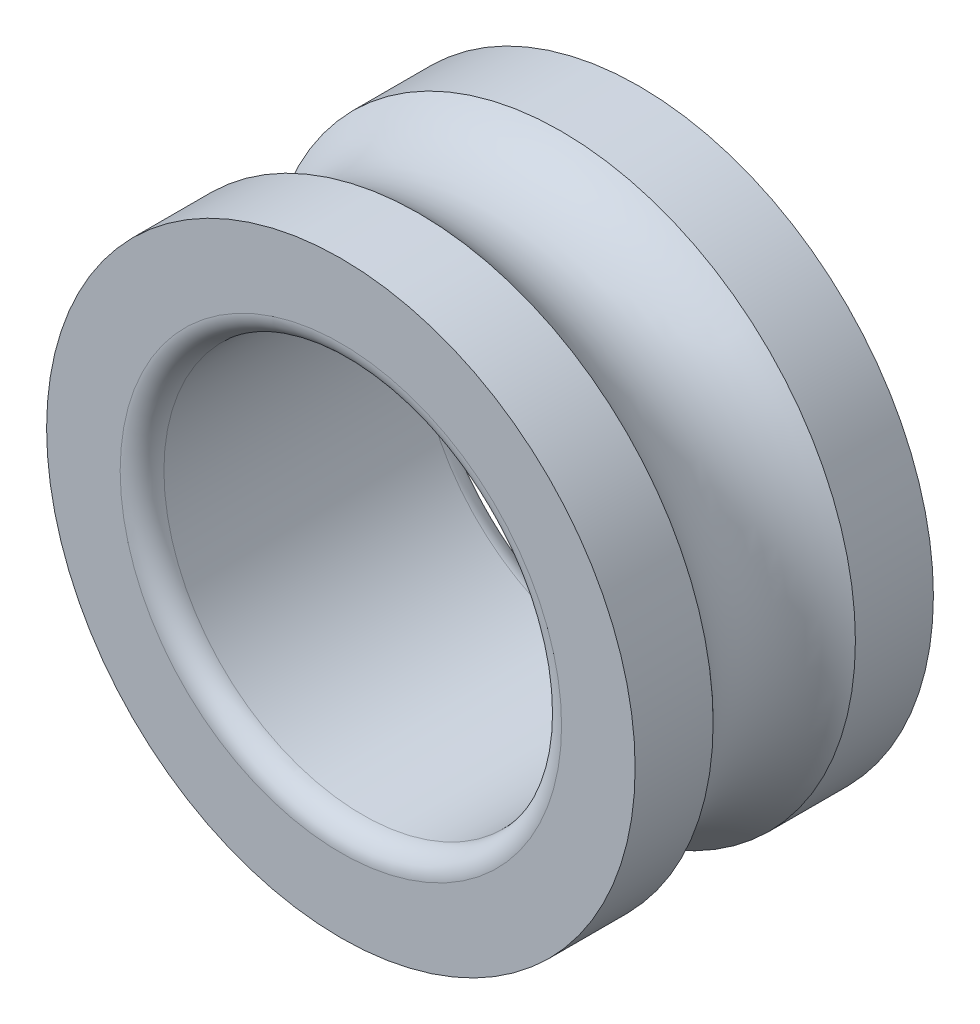
SolidWorks part; units mm, degrees
ref_plane "Plan de face" through (0, 0, 0) normal (0, 0, 1) x (1, 0, 0)
ref_plane "Plan de dessus" through (0, 0, 0) normal (0, 1, 0) x (1, 0, 0)
ref_plane "Plan de droite" through (0, 0, 0) normal (1, 0, 0) x (0, 0, -1)
sketch "Esquisse2" plane through (0, 0, 0) normal (1, 0, 0) x (0, 0, -1)
  line L0 (0, 0) -> (0, 10) construction
  line L1 (0, 10) -> (0, 18) construction
  line L2 (-7.5, 10) -> (7.5, 10)
  line L3 (-7.5, 10) -> (-7.5, 14.8)
  line L4 (-7.5, 14.8) -> (7.5, 14.8)
  line L5 (7.5, 10) -> (7.5, 14.8)
  line L6 (0, 0) -> (-26.6143, 0) construction
  circle A0 centre (0, 18) radius 4.8
  dimension "D5" = 9.6
  dimension "D1" = 15
  dimension "D2" = 10
  dimension "D3" = 14.8
  dimension "D4" = 18
revolve "Révolution1" add sketch "Esquisse2" angle 360 about L6
fillet "Congé1" radius 1.1 2 edges at (-10, 0, 7.5) (-10, 0, -7.5)
scale "Echelle1" scale about centroid uniform scaling yes scale factor 0.69
